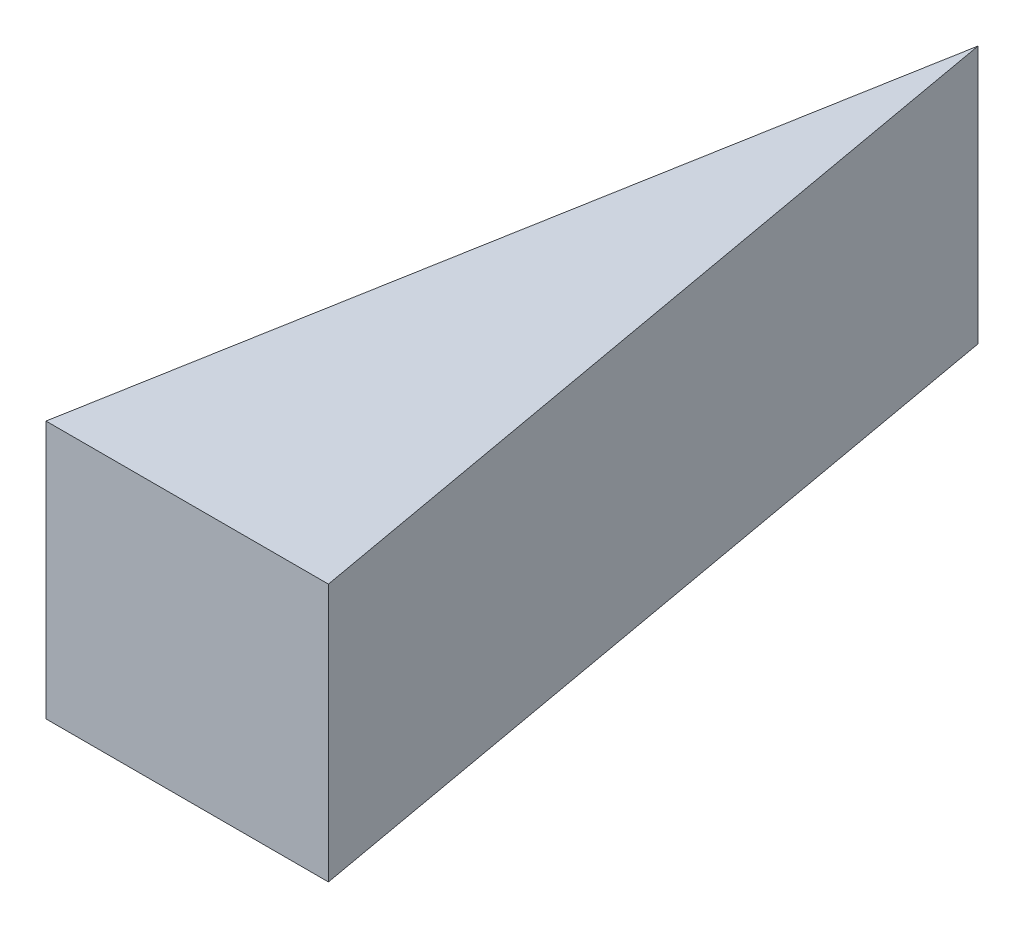
SolidWorks part; units mm, degrees
material "AISI 4340 Steel, annealed"
ref_plane "Front Plane" through (0, 0, 0) normal (0, 0, 1) x (1, 0, 0)
ref_plane "Top Plane" through (0, 0, 0) normal (0, 1, 0) x (1, 0, 0)
ref_plane "Right Plane" through (0, 0, 0) normal (1, 0, 0) x (0, 0, -1)
sketch "Sketch1" plane through (0, 0, 0) normal (0, 1, 0) x (1, 0, 0)
  line L0 (0, 0) -> (-71.265, -399.0667)
  line L1 (-71.265, -399.0667) -> (71.265, -399.0667)
  line L2 (71.265, -399.0667) -> (0, 0)
  point P4 (0, -399.0667)
  dimension "D1" = 405.38
  dimension "D2" = 142.53
extrude "Main block extrude" add sketch "Sketch1" along normal mid plane 130.18
shell "Shell1" thickness 5
